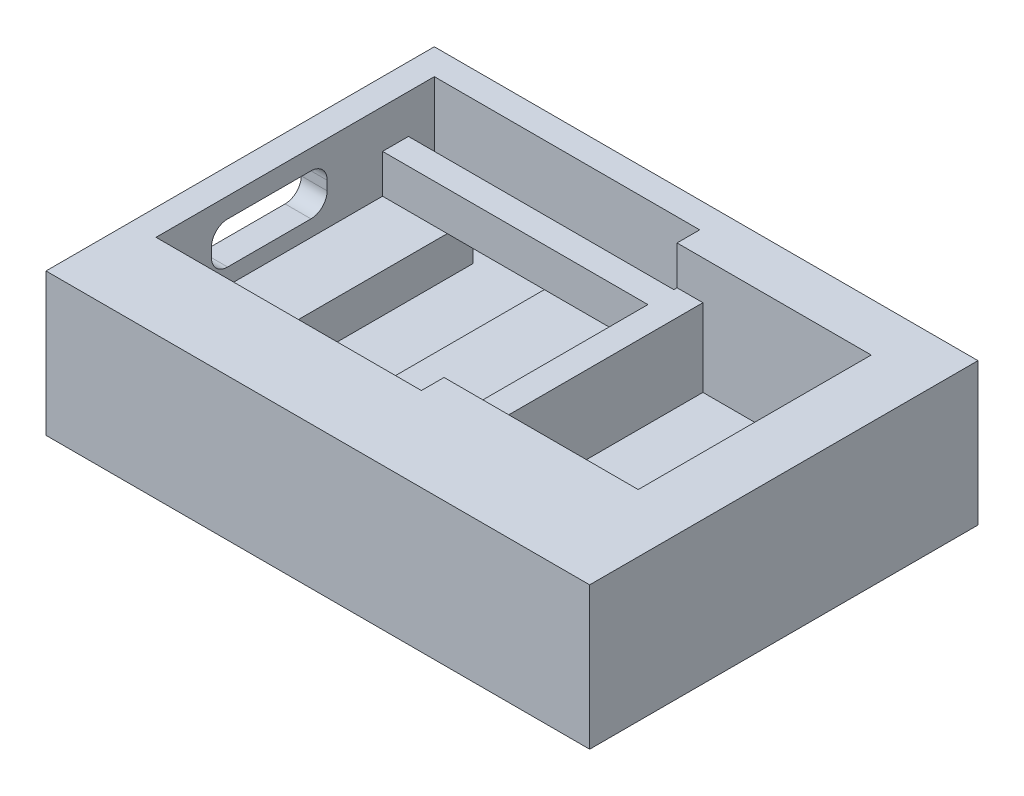
SolidWorks part; units mm, degrees
ref_plane "Front Plane" through (0, 0, 0) normal (0, 0, 1) x (1, 0, 0)
ref_plane "Top Plane" through (0, 0, 0) normal (0, 1, 0) x (1, 0, 0)
ref_plane "Right Plane" through (0, 0, 0) normal (1, 0, 0) x (0, 0, -1)
sketch "Sketch1" plane through (0, 0, 0) normal (0, 1, 0) x (1, 0, 0)
  line L1 (0, 25.5) -> (24.5, 25.5)
  line L2 (0, 25.5) -> (0, 0)
  line L3 (0, 0) -> (24.5, 0)
  line L4 (39.5, 23.75) -> (39.5, 1.75)
  line L7 (39.5, 23.75) -> (24.5, 23.75)
  line L8 (24.5, 25.5) -> (24.5, 23.75)
  line L11 (39.5, 1.75) -> (24.5, 1.75)
  line L12 (24.5, 0) -> (24.5, 1.75)
  dimension "D1" = 1.75
  dimension "D2" = 1.75
  dimension "D3" = 22
  dimension "D4" = 15
  dimension "D5" = 24.5
  dimension "D6" = 24.5
extrude "Boss-Extrude1" add sketch "Sketch1" along normal blind 2 contours L1 L2 L3 L12 L11 L4 L7 L8
sketch "Sketch2" plane through (0, 2, 0) normal (0, 1, 0) x (1, 0, 0)
  line L0 (24.5, 23.75) -> (24.5, 25.5)
  line L1 (24.5, 25.5) -> (0, 25.5)
  line L2 (0, 25.5) -> (0, 0)
  line L3 (0, 0) -> (24.5, 0)
  line L4 (24.5, 0) -> (24.5, 1.75)
  line L5 (24.5, 1.75) -> (39.5, 1.75)
  line L6 (39.5, 1.75) -> (39.5, 23.75)
  line L7 (39.5, 23.75) -> (24.5, 23.75)
  line L8 (2, 21.5) -> (2, 23.5)
  line L9 (24.5, 21.75) -> (37.5, 21.75)
  line L10 (24.5, 21.75) -> (24.5, 3.75)
  line L11 (24.5, 3.75) -> (37.5, 3.75)
  line L12 (37.5, 21.75) -> (37.5, 3.75)
  line L13 (2, 2) -> (22.5, 2)
  line L14 (2, 2) -> (2, 19.5)
  line L15 (2, 23.5) -> (22.5, 23.5)
  line L16 (22.5, 2) -> (22.5, 19.5)
  line L17 (2, 21.5) -> (22.5, 21.5)
  line L19 (2, 19.5) -> (22.5, 19.5)
  line L21 (22.5, 21.5) -> (22.5, 23.5)
  dimension "D1" = 2
  dimension "D2" = 2
  dimension "D3" = 2
  dimension "D4" = 2
  dimension "D5" = 2
  dimension "D6" = 2
  dimension "D7" = 2
  dimension "D8" = 20.5
  dimension "D9" = 2
  dimension "D10" = 2
extrude "Boss-Extrude2" add sketch "Sketch2" along normal blind 9
sketch "Sketch3" plane through (0, 0, -19.5) normal (0, 0, 1) x (1, 0, 0)
  line L1 (2, 2) -> (7, 2)
  line L2 (2, 2) -> (2, 5)
  line L3 (2, 5) -> (7, 5)
  line L4 (7, 2) -> (7, 5)
  line L5 (22.5, 2) -> (14.5, 2)
  line L6 (22.5, 2) -> (22.5, 5)
  line L7 (22.5, 5) -> (14.5, 5)
  line L8 (14.5, 2) -> (14.5, 5)
  dimension "D1" = 3
  dimension "D2" = 8
  dimension "D3" = 5
  dimension "D4" = 3
extrude "Boss-Extrude4" add sketch "Sketch3" along normal blind 17.5 contours L8 L7 L6 L5 | L4 L3 L2 L1
sketch "Sketch6" plane through (0, 0, -19.5) normal (0, 0, 1) x (1, 0, 0)
  line L1 (7, 5) -> (14.5, 5)
  line L2 (7, 5) -> (7, 2)
  line L3 (7, 2) -> (14.5, 2)
  line L4 (14.5, 5) -> (14.5, 2)
extrude "Cut-Extrude1" cut sketch "Sketch6" against normal blind 2.5
sketch "Sketch7" plane through (0, 11, 0) normal (0, 1, 0) x (1, 0, 0)
  line L1 (24.5, 3.75) -> (22.5, 3.75)
  line L2 (24.5, 3.75) -> (24.5, 19.5)
  line L4 (22.5, 3.75) -> (22.5, 19.5)
  line L5 (22.5, 19.5) -> (2, 19.5)
  line L6 (24.5, 19.5) -> (24.5, 21.5)
  line L7 (22.5, 21.5) -> (2, 21.5)
  line L8 (2, 19.5) -> (2, 21.5)
  line L9 (24.5, 21.75) -> (22.5, 21.75)
  line L10 (24.5, 21.75) -> (24.5, 21.5)
  line L12 (22.5, 21.75) -> (22.5, 21.5)
extrude "Cut-Extrude3" cut sketch "Sketch7" against normal blind 3
sketch "Sketch11" plane through (0, 0, -1.75) normal (0, 0, 1) x (1, 0, 0)
  line L1 (39.5, 0) -> (24.5, 0)
  line L2 (39.5, 0) -> (39.5, 11)
  line L3 (39.5, 11) -> (24.5, 11)
  line L4 (24.5, 0) -> (24.5, 11)
extrude "Boss-Extrude5" add sketch "Sketch11" along normal blind 1.75
sketch "Sketch12" plane through (0, 0, -23.75) normal (0, 0, -1) x (-1, 0, 0)
  line L0 (-39.5, 0) -> (-24.5, 0) construction
  line L1 (-39.5, 0) -> (-24.5, 0)
  line L2 (-39.5, 0) -> (-39.5, 11)
  line L3 (-39.5, 11) -> (-24.5, 11)
  line L4 (-24.5, 0) -> (-24.5, 11)
  line L5 (-39.5, 11) -> (-39.5, 0) construction
extrude "Boss-Extrude6" add sketch "Sketch12" along normal blind 1.75 contours L2 L1 L4 L3
sketch "Sketch13" plane through (2, 0, 0) normal (1, 0, 0) x (0, 0, -1)
  line L0 (6.28, 7.5) -> (6.28, 8.21)
  line L1 (7.53, 6.25) -> (13.97, 6.25)
  line L2 (7.53, 9.46) -> (13.97, 9.46)
  line L3 (15.22, 8.21) -> (15.22, 7.5)
  line L4 (2, 5) -> (19.5, 5) construction
  line L5 (19.5, 8) -> (19.5, 5) construction
  arc A0 (6.28, 7.5) -> (7.53, 6.25) centre (7.53, 7.5) ccw
  arc A1 (7.53, 9.46) -> (6.28, 8.21) centre (7.53, 8.21) ccw
  arc A2 (15.22, 8.21) -> (13.97, 9.46) centre (13.97, 8.21) ccw
  arc A3 (13.97, 6.25) -> (15.22, 7.5) centre (13.97, 7.5) ccw
  dimension "D1" = 1.25
  dimension "D9" = 1.25
  dimension "D10" = 3.21
  dimension "D2" = 0.71
  dimension "D3" = 6.44
  dimension "D4" = 1.25
  dimension "D5" = 1.25
  dimension "D6" = 1.25
  dimension "D7" = 5.53
  dimension "D8" = 6.44
  dimension "D11" = 0.71
extrude "Cut-Extrude4" cut sketch "Sketch13" against normal blind 2
sketch "Sketch14" plane through (0, 0, 0) normal (0, 0, 1) x (1, 0, 0)
  line L1 (0, 11) -> (39.5, 11)
  line L2 (0, 11) -> (0, 0)
  line L3 (0, 0) -> (39.5, 0)
  line L4 (39.5, 11) -> (39.5, 0)
extrude "Boss-Extrude7" add sketch "Sketch14" along normal blind 4.5
sketch "Sketch16" plane through (39.5, 0, 0) normal (1, 0, 0) x (0, 0, -1)
  line L1 (-4.5, 11) -> (25.5, 11)
  line L2 (-4.5, 11) -> (-4.5, 0)
  line L3 (-4.5, 0) -> (25.5, 0)
  line L4 (25.5, 11) -> (25.5, 0)
extrude "Boss-Extrude8" add sketch "Sketch16" along normal blind 2.5
